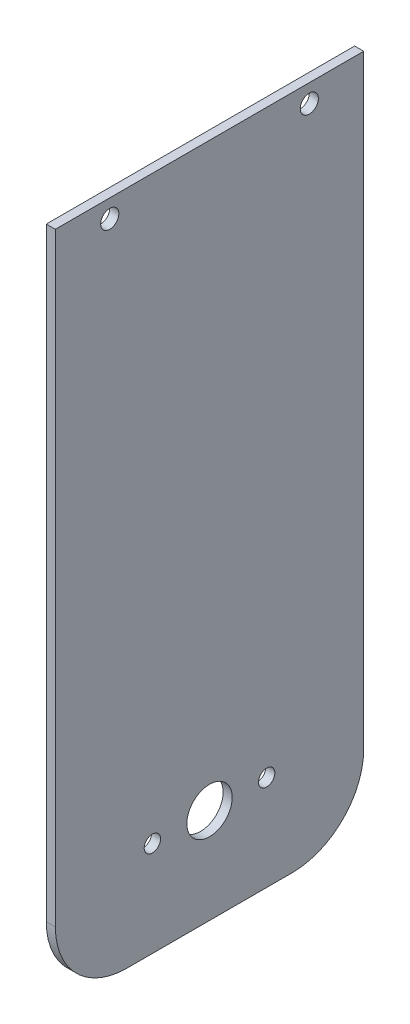
SolidWorks part; units mm, degrees
material "6061-T6 (SS)"
ref_plane "Front Plane" through (0, 0, 0) normal (0, 0, 1) x (1, 0, 0)
ref_plane "Top Plane" through (0, 0, 0) normal (0, 1, 0) x (1, 0, 0)
ref_plane "Right Plane" through (0, 0, 0) normal (1, 0, 0) x (0, 0, -1)
sketch "Sketch1" plane through (0, 0, 0) normal (1, 0, 0) x (0, 0, -1)
  line L0 (-53.975, -84.9275) -> (53.975, -84.9275) construction
  line L1 (-53.975, 118.2675) -> (53.975, 118.2675)
  line L2 (-53.975, 118.2675) -> (-53.975, -118.2675)
  line L3 (-53.975, -118.2675) -> (53.975, -118.2675)
  line L4 (53.975, 118.2675) -> (53.975, -118.2675)
  line L5 (-53.975, 118.2675) -> (53.975, -118.2675) construction
  line L6 (-53.975, -118.2675) -> (53.975, 118.2675) construction
  line L7 (-53.975, 111.9175) -> (53.975, 111.9175) construction
  line L8 (-34.925, 111.9175) -> (-34.925, 115.0925) construction
  line L9 (34.925, 111.9175) -> (34.925, 115.0925) construction
  line L10 (-53.975, 111.9175) -> (-34.925, 111.9175) construction
  line L11 (34.925, 111.9175) -> (53.975, 111.9175) construction
  circle A0 centre (0, -84.9275) radius 7.94
  circle A1 centre (20, -84.9275) radius 2.86
  circle A2 centre (-20, -84.9275) radius 2.86
  circle A3 centre (-34.925, 111.9175) radius 3.175
  circle A4 centre (34.925, 111.9175) radius 3.175
  point P0 (0, 0)
  point P20 (0, 0)
  point P23 (0, 0)
  dimension "D4" = 15.88
  dimension "D6" = 5.72
  dimension "D7" = 5.72
  dimension "D9" = 12.2102
  dimension "D1" = 236.535
  dimension "D2" = 107.95
  dimension "D3" = 33.34
  dimension "D5" = 20
  dimension "D8" = 20
  dimension " 1in/2" = 6.35
  dimension "D10" = 19.05
  dimension "D11" = 19.05
extrude "Boss-Extrude1" add sketch "Sketch1" along normal blind 3.175
fillet "Fillet1" radius 25 2 edges at (1.5875, -118.2675, 53.975) (1.5875, -118.2675, -53.975)
